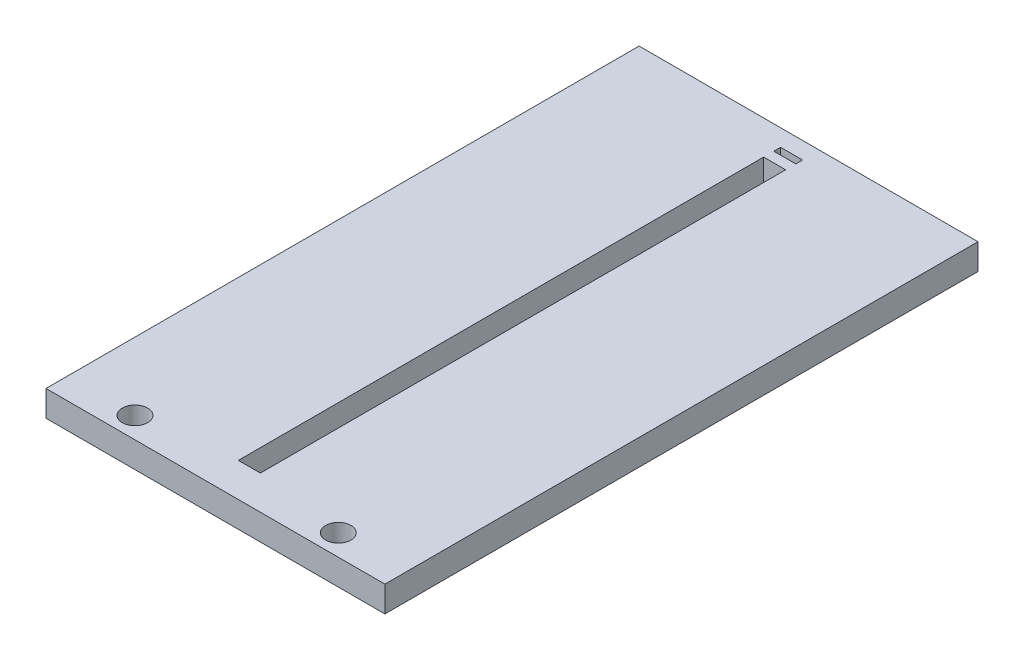
SolidWorks part; units mm, degrees
ref_plane "Front Plane" through (0, 0, 0) normal (0, 0, 1) x (1, 0, 0)
ref_plane "Top Plane" through (0, 0, 0) normal (0, 1, 0) x (1, 0, 0)
ref_plane "Right Plane" through (0, 0, 0) normal (1, 0, 0) x (0, 0, -1)
sketch "Sketch1" plane through (0, 0, 0) normal (0, 1, 0) x (1, 0, 0)
  line L1 (0, 0) -> (40, 0)
  line L2 (0, 0) -> (0, 70)
  line L3 (0, 70) -> (40, 70)
  line L4 (40, 0) -> (40, 70)
  dimension "D1" = 40
  dimension "D2" = 70
extrude "Boss-Extrude1" add sketch "Sketch1" along normal blind 3.05
sketch "Sketch4" plane through (0, 3.05, 0) normal (0, 1, 0) x (1, 0, 0)
  line L0 (20, 70) -> (20, 68)
  line L1 (0, 70) -> (40, 70) construction
  line L2 (20, 4) -> (20, 0)
  line L3 (21.3, 68) -> (18.7, 68)
  line L4 (18.7, 68) -> (18.7, 67.2)
  line L5 (18.7, 67.2) -> (21.3, 67.2)
  line L6 (21.3, 67.2) -> (21.3, 68)
  line L7 (20, 67.2) -> (20, 66)
  line L8 (0, 0) -> (40, 0) construction
  line L9 (21.3, 66) -> (18.7, 66)
  line L10 (18.7, 66) -> (18.7, 4)
  line L11 (18.7, 4) -> (21.3, 4)
  line L12 (21.3, 4) -> (21.3, 66)
  point P10 (20, 68)
  point P22 (20, 66)
  dimension "D1" = 2
  dimension "D2" = 0.8
  dimension "D3" = 1.2
  dimension "D4" = 2.6
  dimension "D5" = 4
  dimension "D6" = 2.6
extrude "Cut-Extrude1" cut sketch "Sketch4" against normal blind 10 contours L11 L12 L9 L10 | L5 L6 L3 L4
sketch "Sketch5" plane through (0, 3.05, 0) normal (0, 1, 0) x (1, 0, 0)
  line L0 (0, 70) -> (0, 30)
  line L1 (0, 0) -> (0, 70) construction
  line L2 (0, 70) -> (15, 70)
  line L3 (0, 70) -> (40, 70) construction
  line L5 (40, 70) -> (25, 70)
  line L6 (40, 70) -> (40, 30)
  line L7 (40, 0) -> (40, 70) construction
  line L9 (15, 70) -> (15, 30)
  line L10 (15, 30) -> (0, 30)
  line L11 (25, 70) -> (25, 30)
  line L12 (25, 30) -> (40, 30)
  circle A0 centre (7.5, 37.5) radius 7.5
  circle A1 centre (32.5, 37.5) radius 7.5
  line M14 (40, 0) -> (40, 70)
  line M15 (40, 70) -> (0, 70)
  line M16 (0, 70) -> (0, 0)
  dimension "D1" = 40
  dimension "D2" = 15
  dimension "D3" = 40
  dimension "D4" = 15
extrude "Cut-Extrude2" [suppressed] cut sketch "Sketch5" against normal blind 10 contours A0 L9 M15 M16 | A0 | A0 L0 L10 | A1 L6 L11 M15 | A1 | A1 L12 M14
sketch "Sketch7" plane through (0, 3.05, 0) normal (0, 1, 0) x (1, 0, 0)
  line L0 (0, 0) -> (8, 0)
  line L1 (0, 0) -> (40, 0) construction
  line L2 (8, 0) -> (8, 2.5)
  line L3 (8, 2.5) -> (32, 2.5)
  circle A0 centre (8, 2.5) radius 1.5
  circle A1 centre (32, 2.5) radius 1.5
  dimension "D3" = 3
  dimension "D5" = 3
  dimension "D1" = 8
  dimension "D2" = 2.5
  dimension "D4" = 24
extrude "Cut-Extrude4" cut sketch "Sketch7" against normal blind 10
